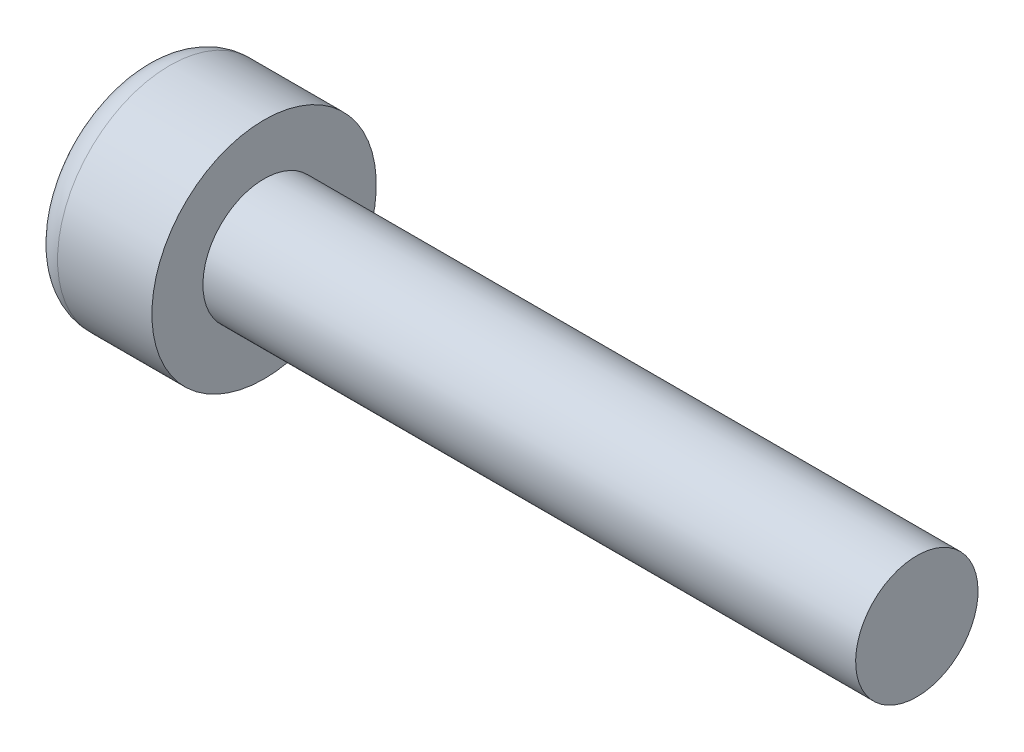
SolidWorks part; units mm, degrees
material "Plain Carbon Steel"
ref_plane "Front Plane" through (0, 0, 0) normal (0, 0, 1) x (1, 0, 0)
ref_plane "Top Plane" through (0, 0, 0) normal (0, 1, 0) x (1, 0, 0)
ref_plane "Right Plane" through (0, 0, 0) normal (1, 0, 0) x (0, 0, -1)
sketch "Sketch1" plane through (0, 0, 0) normal (0, 0, 1) x (1, 0, 0)
  line L0 (0, 0) -> (0, 2.0625)
  line L1 (0.6875, 2.75) -> (3, 2.75)
  line L2 (3, 2.75) -> (3, 1.5)
  line L3 (3, 1.5) -> (19, 1.5)
  line L4 (19, 1.5) -> (19, 0)
  line L5 (19, 0) -> (0, 0) construction
  line L6 (0.6875, 2.0625) -> (0.6875, 1.375) construction
  line L7 (0.6875, 1.375) -> (0.6875, 0.6875) construction
  line L8 (0.6875, 0.6875) -> (0.6875, 0) construction
  line L9 (0.6875, 2.75) -> (0.6875, 2.0625) construction
  line L10 (0, 0) -> (19, 0)
  arc A0 (0, 2.0625) -> (0.6875, 2.75) centre (0.6875, 2.0625) cw
  dimension "D1" = 3
  dimension "D2" = 5.5
  dimension "D3" = 3
  dimension "D4" = 16
revolve "Revolve1" add sketch "Sketch1" angle 360 about L10
sketch "Sketch2" plane through (0, 0, 0) normal (-1, 0, 0) x (0, 0, 1)
  line L1 (0, 1.4434) -> (-1.25, 0.7217)
  line L2 (-1.25, 0.7217) -> (-1.25, -0.7217)
  line L3 (-1.25, -0.7217) -> (0, -1.4434)
  line L4 (0, -1.4434) -> (1.25, -0.7217)
  line L5 (1.25, -0.7217) -> (1.25, 0.7217)
  line L6 (1.25, 0.7217) -> (0, 1.4434)
  circle A0 centre (0, 0) radius 1.25 construction
  dimension "D1" = 2.5
extrude "Cut-Extrude1" cut sketch "Sketch2" against normal blind 1.5
